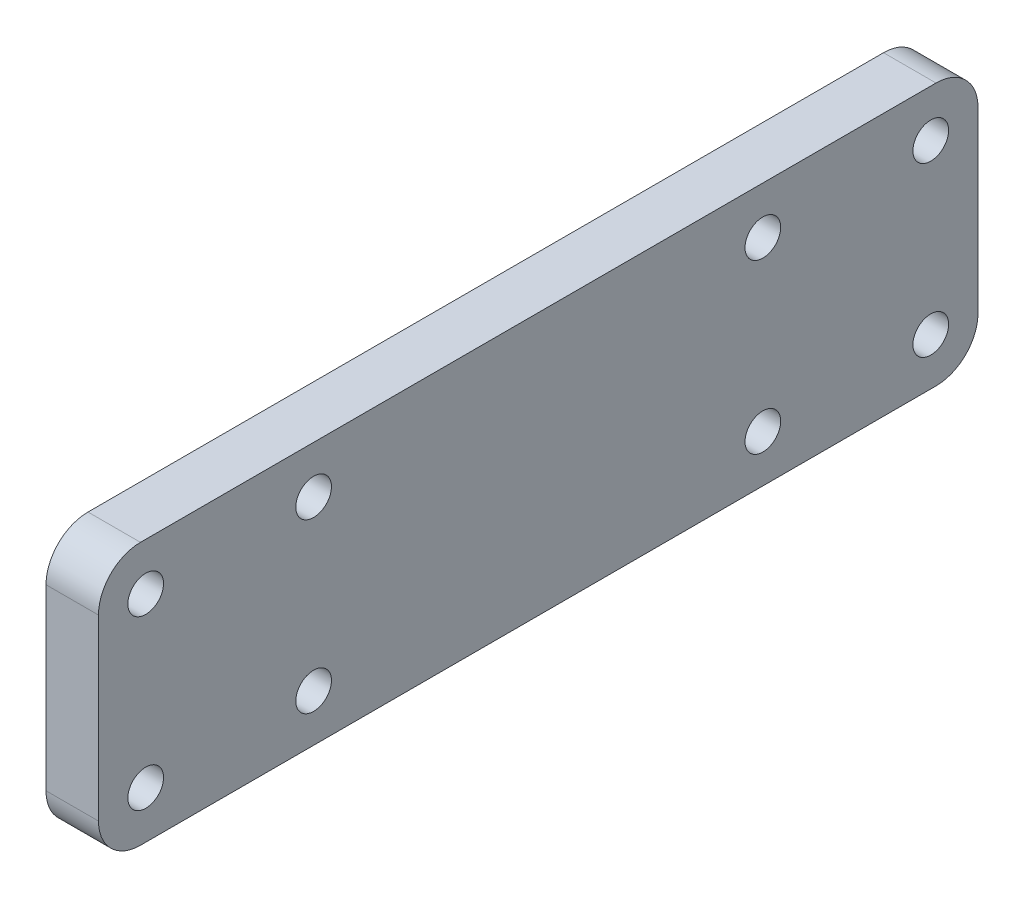
SolidWorks part; units mm, degrees
ref_plane "Plan de face" through (0, 0, 0) normal (0, 0, 1) x (1, 0, 0)
ref_plane "Plan de dessus" through (0, 0, 0) normal (0, 1, 0) x (1, 0, 0)
ref_plane "Plan de droite" through (0, 0, 0) normal (1, 0, 0) x (0, 0, -1)
sketch "Esquisse1" plane through (0, 0, 0) normal (0, 0, 1) x (1, 0, 0)
  line L0 (0, 12.5) -> (0, -12.5)
  line L1 (0, -12.5) -> (5, -12.5)
  line L2 (5, -12.5) -> (5, 12.5)
  line L3 (5, 12.5) -> (0, 12.5)
  dimension "D1" = 25
  dimension "D2" = 5
extrude "Boss.-Extru.1" add sketch "Esquisse1" along normal blind 83.8029
fillet "Congé1" radius 4 4 edges at (2.5, -12.5, 83.8029) (2.5, 12.5, 83.8029) (2.5, -12.5, 0) (2.5, 12.5, 0)
hole_wizard "Dégagement M31" positions "Esquisse2" profile "Esquisse3" hole size "M3" standard "DIN" end condition through all
sketch "Esquisse2" plane through (5, 0, 0) normal (1, 0, 0) x (0, 0, -1)
  line L1 (0, -8.5) -> (0, 8.5) construction
  line L3 (-4.5, 8) -> (0, 8) construction
  line L6 (-4.5, 8) -> (-4.5, 12.5) construction
  line L7 (-79.8029, 12.5) -> (-4, 12.5) construction
  line L10 (-79.3029, 8) -> (-83.8029, 8) construction
  line L11 (-83.8029, -8.5) -> (-83.8029, 8.5) construction
  point P0 (-4.5, -8)
  point P2 (-4.5, 8)
  point P4 (-20.5, 8)
  point P6 (-63.3029, 8)
  point P8 (-79.3029, 8)
  point P10 (-79.3029, -8)
  point P12 (-63.3029, -8)
  point P14 (-20.5, -8)
  point P27 (0, 0)
  dimension "D1" = 16
  dimension "D2" = 8
  dimension "D3" = 16
  dimension "D4" = 16
sketch "Esquisse3" plane through (5, -8, 4.5) normal (0, 1, 0) x (0, 0, -1)
  line L0 (0, 0) -> (0, 5)
  line L1 (0, 5) -> (1.7, 5)
  line L2 (1.7, 5) -> (1.7, 0)
  line L5 (1.7, 0) -> (0, 0)
  line L11 (0, -6.35) -> (0, 107.95) construction
  dimension "Diamètre du perçage jusqu'au prochain" = 3.4
  dimension "Profondeur du perçage jusqu'au prochain" = 5
equation "\"d\"= 16mm"
equation "\"D1@Esquisse2\"=\"d\""
equation "\"D3@Esquisse2\"=\"d\""
equation "\"D4@Esquisse2\"=\"d\""
equation "\"D2@Esquisse2\"=\"d\"/2"
